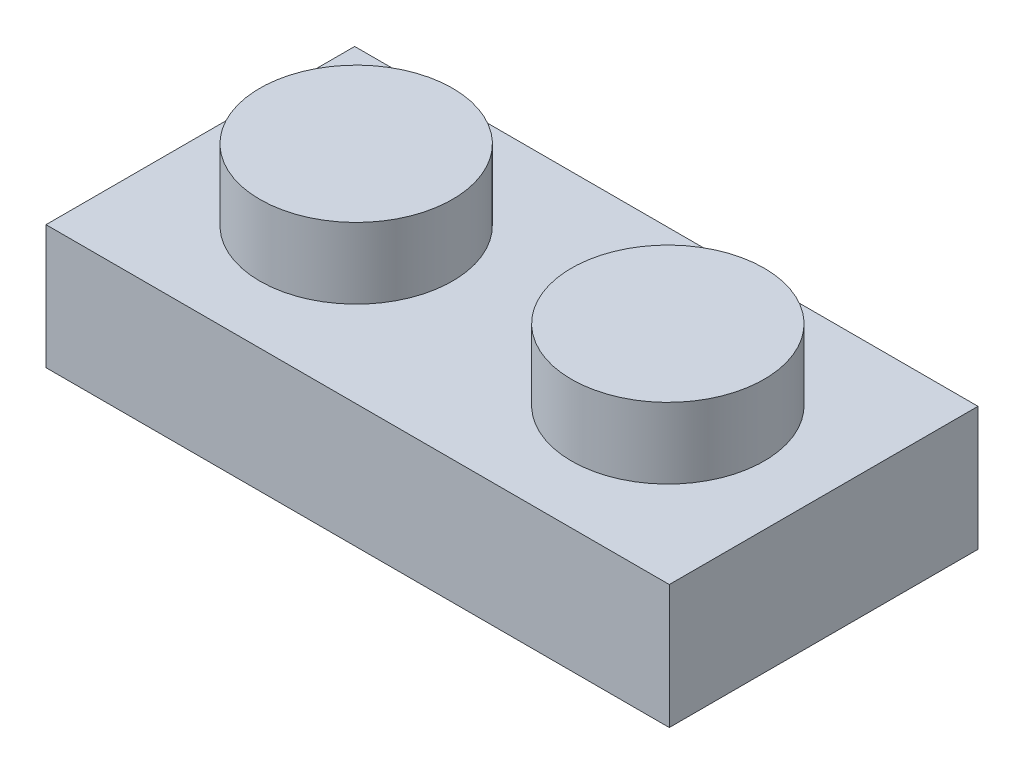
SolidWorks part; units mm, degrees
ref_plane "Front Plane" through (0, 0, 0) normal (0, 0, 1) x (1, 0, 0)
ref_plane "Top Plane" through (0, 0, 0) normal (0, 1, 0) x (1, 0, 0)
ref_plane "Right Plane" through (0, 0, 0) normal (1, 0, 0) x (0, 0, -1)
sketch "Sketch1" plane through (0, 0, 0) normal (0, 1, 0) x (1, 0, 0)
  line L1 (-7.925, 3.925) -> (7.925, 3.925)
  line L2 (-7.925, 3.925) -> (-7.925, -3.925)
  line L3 (-7.925, -3.925) -> (7.925, -3.925)
  line L4 (7.925, 3.925) -> (7.925, -3.925)
  line L5 (-7.925, 3.925) -> (7.925, -3.925) construction
  line L6 (-7.925, -3.925) -> (7.925, 3.925) construction
  point P0 (0, 0)
  dimension "D1" = 15.85
  dimension "D2" = 7.85
extrude "Boss-Extrude1" add sketch "Sketch1" against normal blind 3.15
sketch "Sketch2" plane through (0, 0, 0) normal (0, 1, 0) x (1, 0, 0)
  line L1 (-7.925, 3.925) -> (-7.925, -3.925) construction
  line L2 (7.925, -3.925) -> (7.925, 3.925) construction
  line L3 (7.925, 3.925) -> (-7.925, 3.925) construction
  circle A0 centre (-3.9625, 0) radius 2.45
  circle A1 centre (3.9625, 0) radius 2.45
  dimension "D1" = 4.9
  dimension "D2" = 4.9
  dimension "D4" = 3.9625
  dimension "D3" = 3.9625
  dimension "D5" = 3.925
  dimension "D6" = 3.925
extrude "Boss-Extrude2" add sketch "Sketch2" along normal blind 1.8
shell "Shell1" thickness 1.5
sketch "Sketch3" plane through (0, -1.5, 0) normal (0, -1, 0) x (1, 0, 0)
  circle A0 centre (0, 0) radius 1.5
  circle A1 centre (0, 0) radius 0.7
  dimension "D1" = 3
  dimension "D2" = 1.4
extrude "Boss-Extrude3" add sketch "Sketch3" along normal offset from surface (1.45 mm away) 0.2 up to face at (0, -3.15, 0)
